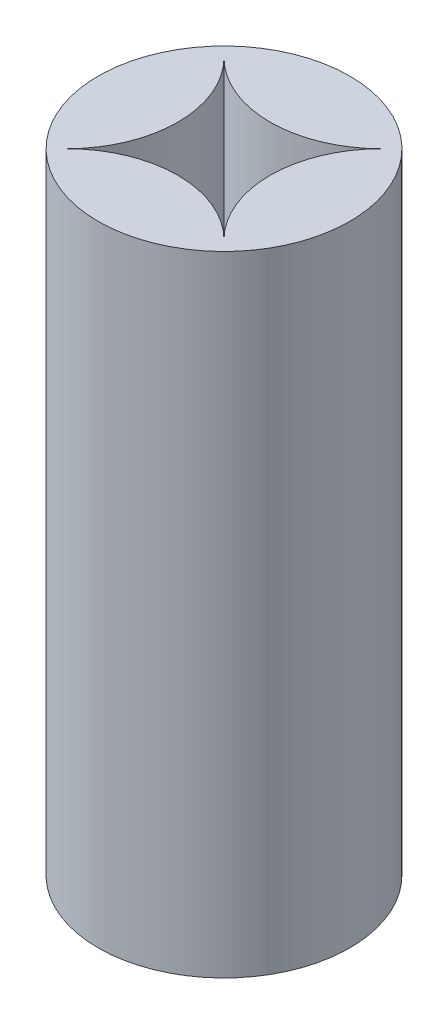
SolidWorks part; units mm, degrees
ref_plane "Front Plane" through (0, 0, 0) normal (0, 0, 1) x (1, 0, 0)
ref_plane "Top Plane" through (0, 0, 0) normal (0, 1, 0) x (1, 0, 0)
ref_plane "Right Plane" through (0, 0, 0) normal (1, 0, 0) x (0, 0, -1)
sketch "Sketch1" plane through (0, 0, 0) normal (0, 1, 0) x (1, 0, 0)
  circle A0 centre (0, 0) radius 4
  dimension "D1" = 8
extrude "Boss-Extrude1" add sketch "Sketch1" along normal blind 20 contours A0
sketch "Sketch2" plane through (0, 20, 0) normal (0, 1, 0) x (1, 0, 0)
  line L5 (-2.5, -2.5) -> (2.5, 2.5) construction
  line L6 (-2.5, 2.5) -> (2.5, -2.5) construction
  arc A4 (2.5, 2.5) -> (-2.5, 2.5) centre (0, 5) cw
  arc A5 (-2.5, 2.5) -> (-2.5, -2.5) centre (-5, 0) cw
  arc A6 (2.5, -2.5) -> (2.5, 2.5) centre (5, 0) cw
  arc A7 (-2.5, -2.5) -> (2.5, -2.5) centre (0, -5) cw
  point P0 (0, 0)
  dimension "D1" = 5
  dimension "D2" = 5
extrude "Cut-Extrude1" cut sketch "Sketch2" against normal blind 10
